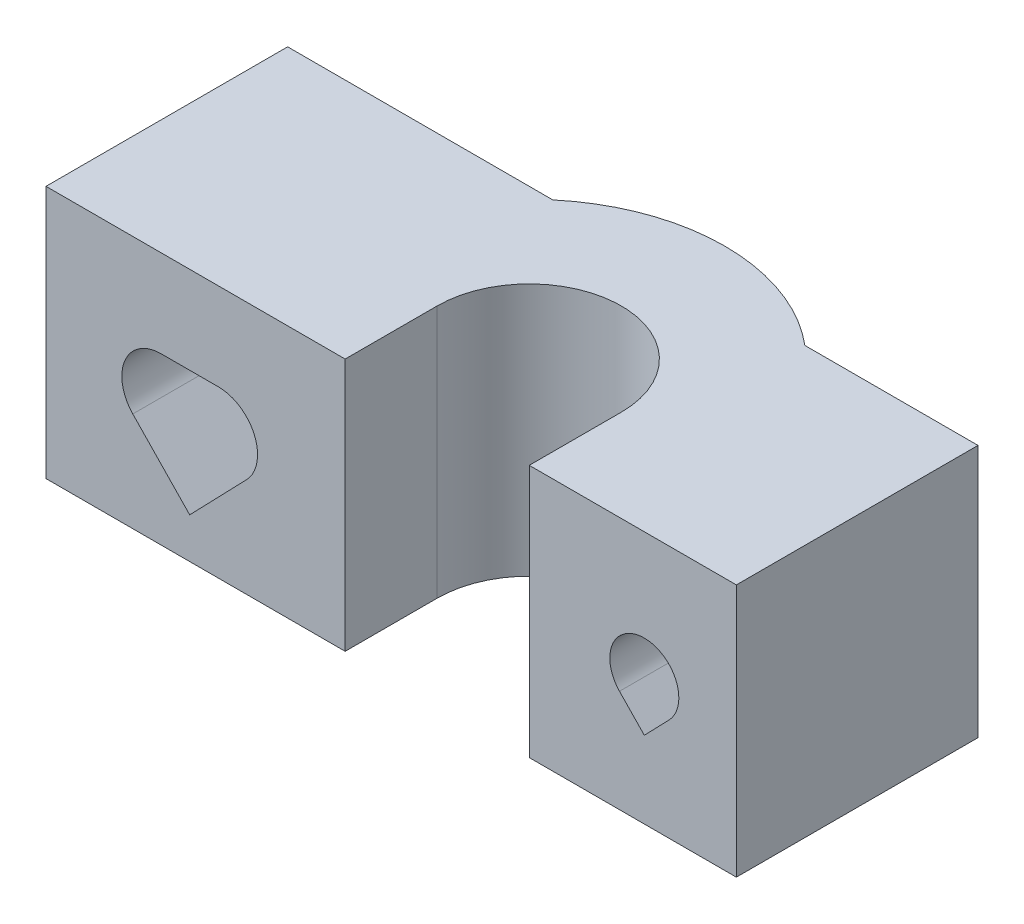
SolidWorks part; units mm, degrees
ref_plane "Front Plane" through (0, 0, 0) normal (0, 0, 1) x (1, 0, 0)
ref_plane "Top Plane" through (0, 0, 0) normal (0, 1, 0) x (1, 0, 0)
ref_plane "Right Plane" through (0, 0, 0) normal (1, 0, 0) x (0, 0, -1)
ref_plane "Plane1" through (0, 11, 0) normal (0, 1, 0) x (-1, 0, 0)
sketch "Sketch1" plane through (0, 11, 0) normal (0, 1, 0) x (-1, 0, 0)
  line L0 (-10, 0) -> (-40, 0)
  line L1 (-40, 0) -> (-40, -10.5)
  line L2 (-40, -10.5) -> (-32.4772, -10.5)
  line L3 (-21.5228, -10.5) -> (-10, -10.5)
  line L4 (-10, -10.5) -> (-10, 0)
  arc A0 (-32.4772, -10.5) -> (-21.5228, -10.5) centre (-27, -4) ccw
  dimension "D5" = 8.5
  dimension "D1" = 30
  dimension "D2" = 10.5
  dimension "D3" = 7.5228
  dimension "D4" = 11.5228
extrude "Boss-Extrude1" add sketch "Sketch1" against normal blind 11
sketch "Sketch2" plane through (0, 0, 0) normal (0, -1, 0) x (1, 0, 0)
  line L0 (31, 0) -> (23, 0)
  line L1 (23, 0) -> (23, -4)
  line L2 (31, -4) -> (31, 0)
  arc A0 (23, -4) -> (31, -4) centre (27, -4) ccw
extrude "Cut-Extrude1" cut sketch "Sketch2" against normal through all
sketch "Sketch3" plane through (0, 0, 0) normal (0, 0, 1) x (1, 0, 0)
  line L0 (34.921, 4.458) -> (36, 3.3407)
  line L1 (36, 3.3407) -> (37.079, 4.458)
  arc A0 (37.079, 4.458) -> (34.921, 4.458) centre (36, 5.5) ccw
extrude "Cut-Extrude2" cut sketch "Sketch3" against normal through all
sketch "Sketch4" plane through (0, 0, -10.5) normal (0, 0, -1) x (-1, 0, 0)
  line L0 (-16.2443, 1.7583) -> (-13.7714, 4.3191)
  line L1 (-14.9943, 7.2) -> (-17.4943, 7.2)
  line L2 (-18.7171, 4.3191) -> (-16.2443, 1.7583)
  arc A0 (-13.7714, 4.3191) -> (-14.9943, 7.2) centre (-14.9943, 5.5) ccw
  arc A1 (-17.4943, 7.2) -> (-18.7171, 4.3191) centre (-17.4943, 5.5) ccw
extrude "Cut-Extrude3" cut sketch "Sketch4" against normal through all
